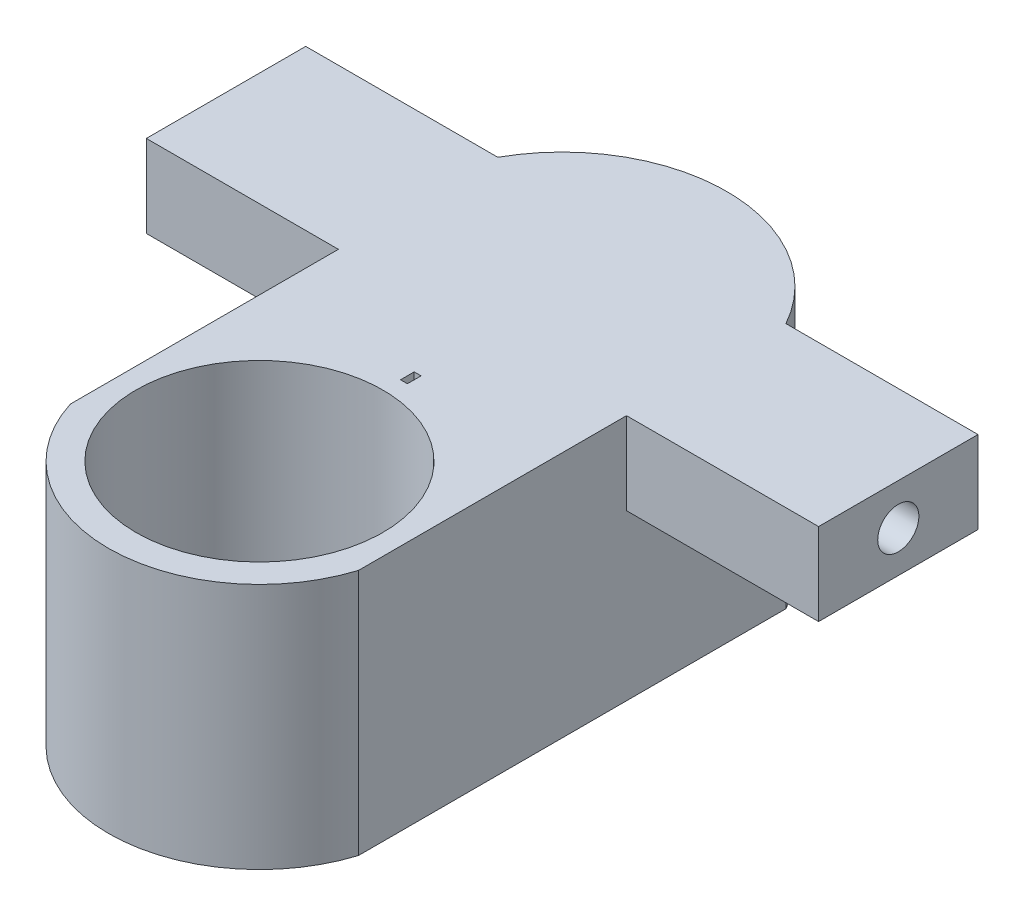
SolidWorks part; units mm, degrees
ref_plane "Płaszczyzna przednia" through (0, 0, 0) normal (0, 0, 1) x (1, 0, 0)
ref_plane "Płaszczyzna górna" through (0, 0, 0) normal (0, 1, 0) x (1, 0, 0)
ref_plane "Płaszczyzna prawa" through (0, 0, 0) normal (1, 0, 0) x (0, 0, -1)
sketch "Sketch1" plane through (0, 0, 0) normal (0, 1, 0) x (1, 0, 0)
  line L0 (0, 0) -> (-10.5, 0)
  line L1 (-10.5, 0) -> (-10.5, 12)
  line L2 (0, 0) -> (0, -12.0652)
  line L3 (-10.5, 12) -> (10.5, 12)
  line L4 (-10.5, 12) -> (-10.5, -12.0652)
  line L5 (-10.5, -12.0652) -> (10.5, -12.0652)
  line L6 (10.5, 12) -> (10.5, -12.0652)
  line L7 (-10.5, -12.0652) -> (-10.5, -32.0652)
  line L8 (-10.5, -32.0652) -> (10.5, -32.0652)
  line L9 (10.5, -32.0652) -> (10.5, -12.0652)
  line L10 (-10.5, -12.0652) -> (-9.5, -12.0652)
  line L11 (-9.5, -12.0652) -> (-9.5, -32.0652)
  line L12 (10.5, -12.0652) -> (9.5, -12.0652)
  line L13 (9.5, -12.0652) -> (9.5, -32.0652)
  line L14 (-10.5, -32.0652) -> (-10.5, -33.0652)
  line L15 (-10.5, -33.0652) -> (10.5, -33.0652)
  line L16 (10.5, -33.0652) -> (10.5, -32.0652)
  line L17 (-9.5, -22.0652) -> (0, -22.0652)
  line L18 (-10.5, -12.0652) -> (-9.5, -12.0652)
  line L19 (-10.5, -12.0652) -> (-10.5, -32.0652)
  line L20 (-10.5, -32.0652) -> (-9.5, -32.0652)
  line L21 (-9.5, -12.0652) -> (-9.5, -32.0652)
  line L22 (-10.5, -33.0652) -> (10.5, -33.0652)
  line L23 (-10.5, -33.0652) -> (-10.5, -32.0652)
  line L24 (-10.5, -32.0652) -> (10.5, -32.0652)
  line L25 (10.5, -33.0652) -> (10.5, -32.0652)
  line L26 (9.5, -12.0652) -> (10.5, -12.0652)
  line L27 (9.5, -12.0652) -> (9.5, -32.0652)
  line L28 (9.5, -32.0652) -> (10.5, -32.0652)
  line L29 (10.5, -12.0652) -> (10.5, -32.0652)
  line L30 (-9.5, -12.0652) -> (9.5, -12.0652)
  line L31 (-9.5, -12.0652) -> (-9.5, -32.0652)
  line L32 (-9.5, -32.0652) -> (9.5, -32.0652)
  line L33 (9.5, -12.0652) -> (9.5, -32.0652)
  line L34 (0, -22.0652) -> (0, -33.0652)
  dimension "D1" = 19
extrude "Boss-Extrude1" add sketch "Sketch1" along normal blind 18
sketch "Sketch2" plane through (0, 18, 0) normal (0, 1, 0) x (1, 0, 0)
  line L0 (0, 0) -> (0, -8.5)
  line L1 (0, 0) -> (8.5, 0)
  circle A0 centre (0, 0) radius 8.5
sketch "Sketch6" plane through (0, 18, 0) normal (0, 1, 0) x (1, 0, 0)
  line L0 (10.5, -33.0652) -> (-10.5, -33.0652)
  line L1 (-10.5, -33.0652) -> (10.5, -33.0652) construction
  line L2 (10.5, 12) -> (10.5, -33.0652) construction
  line L3 (0, -33.0652) -> (0, -22.0652)
  line L5 (-10.5, -33.0652) -> (10.5, -33.0652)
  line L6 (-10.5, -33.0652) -> (-10.5, -12.0652)
  line L7 (-10.5, -12.0652) -> (10.5, -12.0652)
  line L8 (10.5, -33.0652) -> (10.5, -12.0652)
  circle A0 centre (0, -22.0652) radius 9
  circle A1 centre (0, -22.0652) radius 11
  dimension "D1" = 21
extrude "Cut-Extrude4" cut sketch "Sketch6" against normal blind 52
sketch "Sketch8" plane through (0, 18, 0) normal (0, 1, 0) x (1, 0, 0)
  line L0 (-10.5, 12) -> (10.5, 12) construction
  line L1 (-10.5, 12) -> (10.5, 12)
  line L2 (-10.5, 12) -> (-10.5, -12.1368)
  line L3 (-10.5, -12.1368) -> (10.5, -12.1368)
  line L4 (10.5, 12) -> (10.5, -12.1368)
  line L5 (-10.5, -25.3439) -> (-10.5, 12) construction
  line L6 (10.5, 12) -> (10.5, -25.3439) construction
  circle A0 centre (0, 0) radius 12
  line M3 (-10.5, 12) -> (-10.5, -25.3439)
  line M5 (10.5, -25.3439) -> (10.5, 12)
  line M6 (10.5, 12) -> (-10.5, 12)
extrude "Cut-Extrude5" cut sketch "Sketch8" against normal blind 52 contours A0 L1 M3 | A0 M5 M6
sketch "Sketch10" plane through (-10.5, 0, 0) normal (-1, 0, 0) x (0, 0, 1)
  line L0 (-5.8095, 18) -> (5.8095, 18)
  line L1 (-5.8095, 0) -> (-5.8095, 18) construction
  line L2 (25.3439, 18) -> (-5.8095, 18) construction
  line L3 (0, 18) -> (0, 12)
  line L4 (-5.8095, 18) -> (-5.8095, 12)
  line L5 (-5.8095, 12) -> (5.8095, 12)
  line L6 (5.8095, 18) -> (5.8095, 12)
  line M6 (25.3439, 18) -> (-5.8095, 18)
  line M7 (-5.8095, 18) -> (-5.8095, 0)
extrude "Boss-Extrude2" add sketch "Sketch10" along normal blind 14 contours L6 L3 L5 M6 | L5 L3 L0 M7
sketch "Sketch11" plane through (0, 18, 0) normal (0, 1, 0) x (1, 0, 0)
  line L0 (0, -8.5) -> (0, -13.0652)
  line L1 (0, -13.0652) -> (0, -10.7826)
  line L2 (0, -10.7826) -> (-0.5, -10.7826)
  line L3 (-0.5, -10.7826) -> (-0.5, -11.7826)
  line L4 (-0.5, -11.7826) -> (0.5, -11.7826)
  line L5 (0.5, -11.7826) -> (0.5, -10.7826)
  line L6 (0.5, -10.7826) -> (0, -10.7826)
  circle A0 centre (0, -22.0652) radius 9 construction
extrude "Cut-Extrude6" cut sketch "Sketch11" against normal blind 0.5 contours L5 L6 L0 L4
mirror "Mirror1" about plane through (0, 17.5, 0) normal (-1, 0, 0) of "Boss-Extrude2"
sketch "Sketch12" plane through (-24.5, 0, 0) normal (-1, 0, 0) x (0, 0, 1)
  line L0 (-5.8095, 18) -> (-5.8095, 12) construction
  line L1 (-5.8095, 18) -> (-5.8095, 12) construction
  line L10 (0, 18) -> (0, 12)
  line L11 (5.8095, 18) -> (-5.8095, 18) construction
  line L12 (-5.8095, 12) -> (5.8095, 12) construction
  circle A0 centre (0, 15) radius 1.5
  point P0 (-5.8095, 18)
extrude "Cut-Extrude7" cut sketch "Sketch12" against normal blind 10 contours L10 A0 | L10 A0
mirror "Mirror2" about plane through (0, 17.5, 0) normal (-1, 0, 0) of "Cut-Extrude7"
